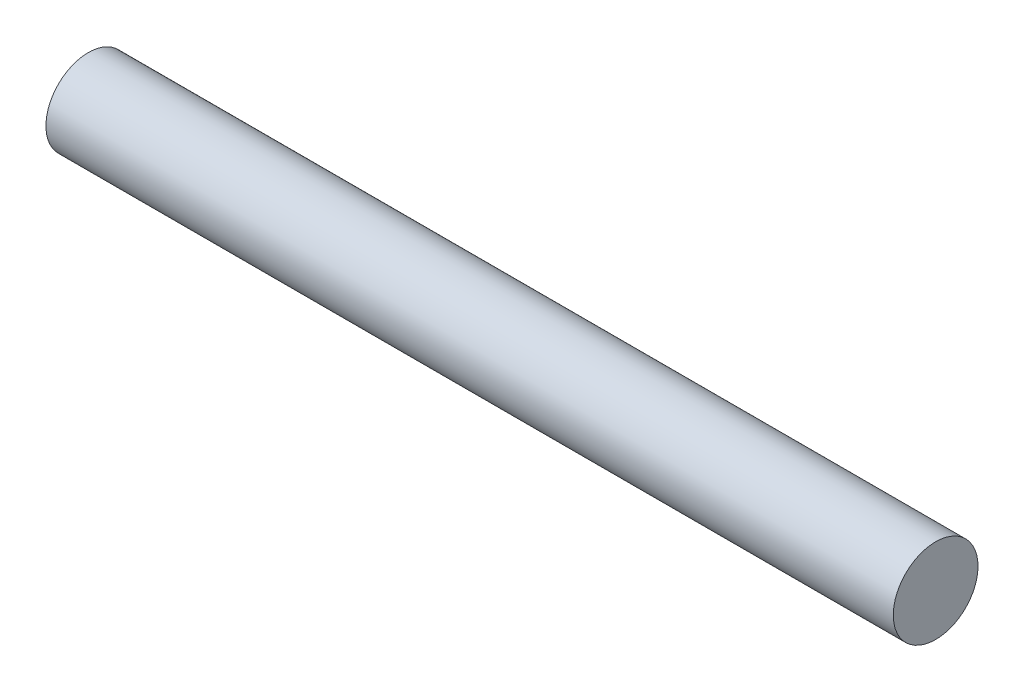
SolidWorks part; units mm, degrees
ref_plane "Front Plane" through (0, 0, 0) normal (0, 0, 1) x (1, 0, 0)
ref_plane "Top Plane" through (0, 0, 0) normal (0, 1, 0) x (1, 0, 0)
ref_plane "Right Plane" through (0, 0, 0) normal (1, 0, 0) x (0, 0, -1)
other "Configuration Table"
sketch "草图1" plane through (0, 0, 0) normal (1, 0, 0) x (0, 0, -1)
  circle A0 centre (0, 0) radius 1.5
  dimension "D1" = 3
extrude "凸台-拉伸1" add sketch "草图1" along normal blind 30
